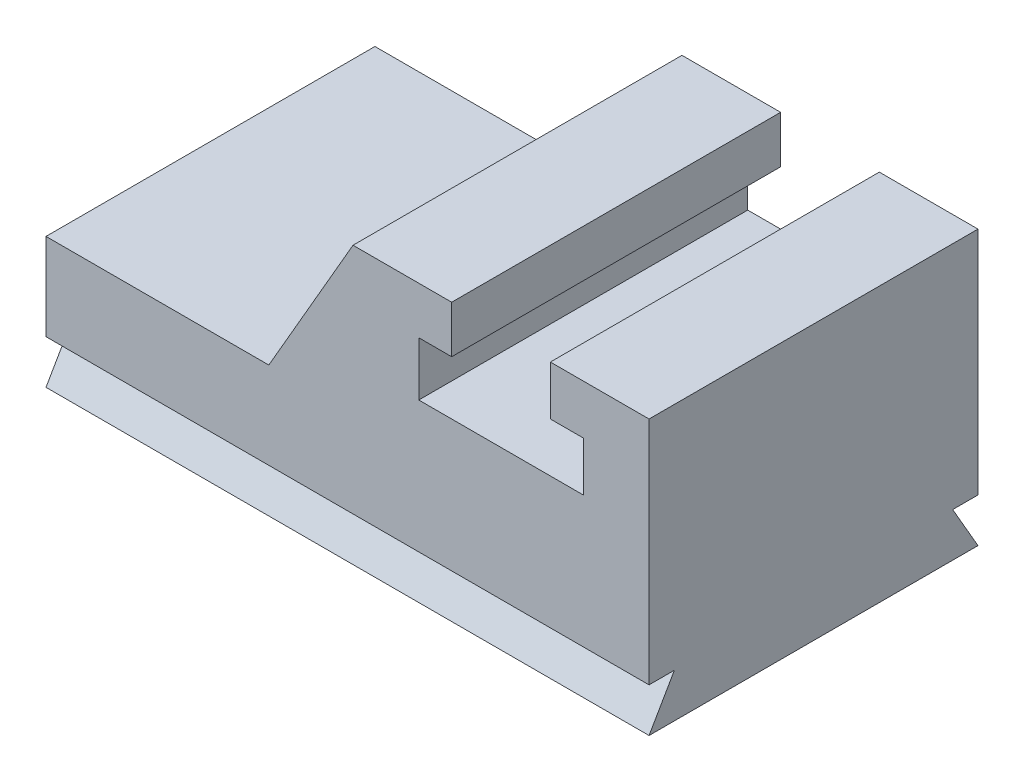
SolidWorks part; units mm, degrees
ref_plane "Front Plane" through (0, 0, 0) normal (0, 0, 1) x (1, 0, 0)
ref_plane "Top Plane" through (0, 0, 0) normal (0, 1, 0) x (1, 0, 0)
ref_plane "Right Plane" through (0, 0, 0) normal (1, 0, 0) x (0, 0, -1)
sketch "Sketch1" plane through (0, 0, 0) normal (0, 0, 1) x (1, 0, 0)
  line L0 (0, 0) -> (110, 0)
  line L1 (110, 0) -> (110, 42)
  line L2 (110, 42) -> (92, 42)
  line L3 (92, 42) -> (92, 33)
  line L4 (92, 33) -> (98, 33)
  line L5 (98, 33) -> (98, 24)
  line L6 (98, 24) -> (68, 24)
  line L7 (68, 24) -> (68, 33.8347)
  line L8 (68, 33.8347) -> (74, 33.8347)
  line L9 (74, 33.8347) -> (74, 42.4486)
  line L10 (74, 42.4486) -> (56, 42.4486)
  line L11 (56, 42.4486) -> (40.6407, 15.8454)
  line L12 (40.6407, 15.8454) -> (0, 15.8454)
  line L13 (0, 15.8454) -> (0, 0)
  dimension "D1" = 110
  dimension "D2" = 42
  dimension "D3" = 18
  dimension "D4" = 9
  dimension "D5" = 6
  dimension "D6" = 9
  dimension "D7" = 30
  dimension "D8" = 18
  dimension "D9" = 18
  dimension "D10" = 60
extrude "Boss-Extrude1" add sketch "Sketch1" along normal blind 60 contours L13 L0 L1 L2 L3 L4 L5 L6 L7 L8 L9 L10 L11 L12
sketch "Sketch2" plane through (0, 0, 0) normal (-1, 0, 0) x (0, 0, 1)
  line L0 (0, 0) -> (0, -8)
  line L1 (0, -8) -> (60, -8)
  line L2 (60, -8) -> (55.3812, 0)
  line L3 (60, 0) -> (0, 0) construction
  line L4 (55.3812, 0) -> (4.6188, 0)
  line L5 (4.6188, 0) -> (0, -8)
  dimension "D1" = 8
  dimension "D2" = 60
  dimension "D3" = 60
  dimension "D4" = 60
extrude "Boss-Extrude2" add sketch "Sketch2" against normal blind 110 contours L1 L2 L4 L5
